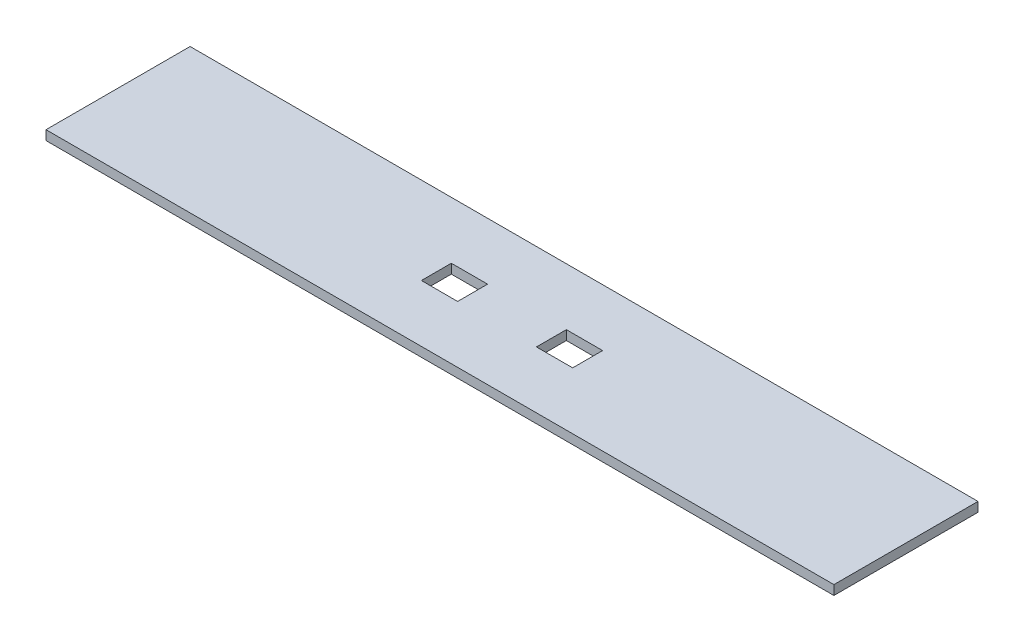
SolidWorks part; units mm, degrees
ref_plane "Front Plane" through (0, 0, 0) normal (0, 0, 1) x (1, 0, 0)
ref_plane "Top Plane" through (0, 0, 0) normal (0, 1, 0) x (1, 0, 0)
ref_plane "Right Plane" through (0, 0, 0) normal (1, 0, 0) x (0, 0, -1)
sketch "Sketch1" plane through (0, 0, 0) normal (0, 1, 0) x (1, 0, 0)
  line L1 (-125, 22.86) -> (125, 22.86)
  line L2 (-125, 22.86) -> (-125, -22.86)
  line L3 (-125, -22.86) -> (125, -22.86)
  line L4 (125, 22.86) -> (125, -22.86)
  line L5 (-125, 22.86) -> (125, -22.86) construction
  line L6 (-125, -22.86) -> (125, 22.86) construction
  point P0 (0, 0)
  dimension "D1" = 45.72
  dimension "D2" = 250
extrude "Boss-Extrude1" add sketch "Sketch1" along normal blind 3
sketch "Sketch2" plane through (0, 0, 0) normal (0, 1, 0) x (1, 0, 0)
  line L1 (-24, 4.75) -> (-12.5, 4.75)
  line L2 (-24, 4.75) -> (-24, -4.75)
  line L3 (-24, -4.75) -> (-12.5, -4.75)
  line L4 (-12.5, 4.75) -> (-12.5, -4.75)
  line L5 (-24, 4.75) -> (-12.5, -4.75) construction
  line L6 (-24, -4.75) -> (-12.5, 4.75) construction
  line L8 (12.5, -4.75) -> (24, -4.75)
  line L9 (12.5, -4.75) -> (12.5, 4.75)
  line L10 (12.5, 4.75) -> (24, 4.75)
  line L11 (24, -4.75) -> (24, 4.75)
  line L12 (12.5, -4.75) -> (24, 4.75) construction
  line L13 (12.5, 4.75) -> (24, -4.75) construction
  point P0 (-18.25, 0)
  point P5 (18.25, 0)
  dimension "D1" = 12.5
  dimension "D2" = 11.5
  dimension "D3" = 9.5
  dimension "D4" = 0
  dimension "D5" = 25
  dimension "D6" = 9.5
  dimension "D7" = 11.5
extrude "Cut-Extrude2" cut sketch "Sketch2" against normal through all both and the other way through all
